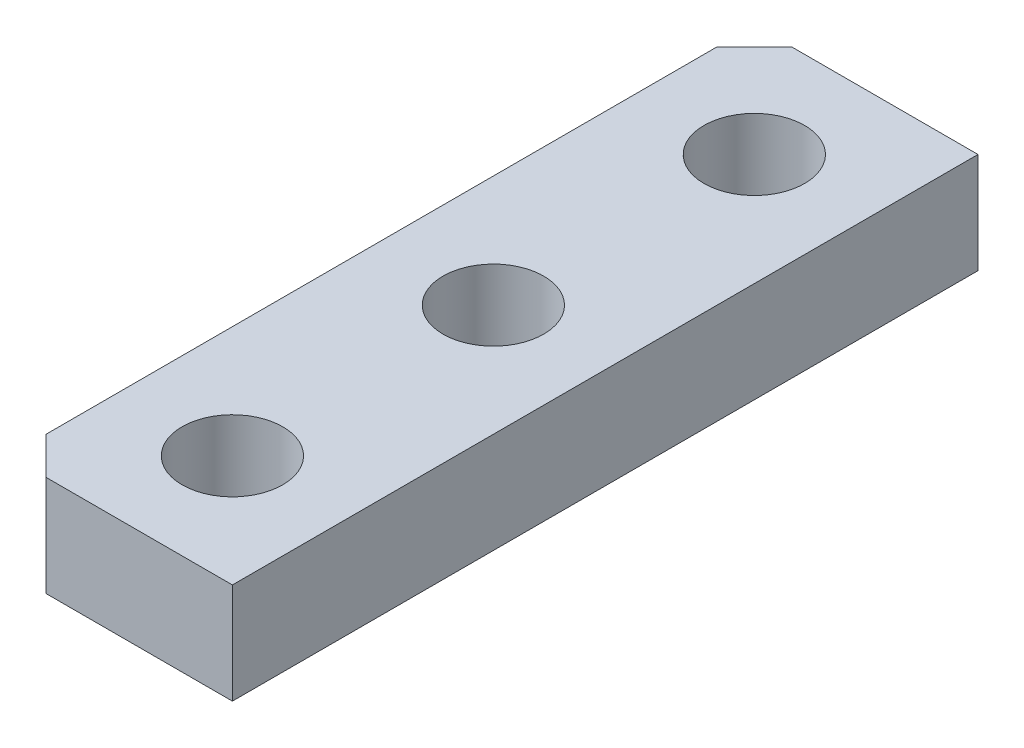
SolidWorks part; units mm, degrees
material "6061 Alloy"
ref_plane "Front Plane" through (0, 0, 0) normal (0, 0, 1) x (1, 0, 0)
ref_plane "Top Plane" through (0, 0, 0) normal (0, 1, 0) x (1, 0, 0)
ref_plane "Right Plane" through (0, 0, 0) normal (1, 0, 0) x (0, 0, -1)
sketch "Sketch1" plane through (0, 0, 0) normal (0, 1, 0) x (1, 0, 0)
  line L1 (15, -50) -> (-15, -50)
  line L2 (15, -50) -> (15, 50)
  line L3 (15, 50) -> (-15, 50)
  line L4 (-15, -50) -> (-15, 50)
  line L5 (15, -50) -> (-15, 50) construction
  line L6 (15, 50) -> (-15, -50) construction
  point P0 (0, 0)
  dimension "D1" = 100
  dimension "D2" = 30
extrude "Boss-Extrude1" add sketch "Sketch1" along normal blind 13.5
hole_wizard "M12 Clearance Hole1" positions "Sketch2" profile "Sketch4" hole size "M12" standard "GB" end condition through all
sketch "Sketch2" plane through (0, 13.5, 0) normal (0, 1, 0) x (1, 0, 0)
  line L0 (0, 35) -> (0, -35) construction
  point P1 (0, 35)
  point P2 (0, -35)
  point P6 (0, 0)
  dimension "D1" = 70
sketch "Sketch4" plane through (0, 13.5, -35) normal (1, 0, 0) x (0, 0, 1)
  line L0 (0, 0) -> (0, 13.5)
  line L1 (0, 13.5) -> (6.75, 13.5)
  line L2 (6.75, 13.5) -> (6.75, 0)
  line L5 (6.75, 0) -> (0, 0)
  line L11 (0, -6.35) -> (0, 107.95) construction
  dimension "Thru Hole Dia." = 13.5
  dimension "Thru Hole Depth" = 13.5
chamfer "Chamfer1" distance 5 angle 45 2 edges at (-15, 6.75, 50) (-15, 6.75, -50)
